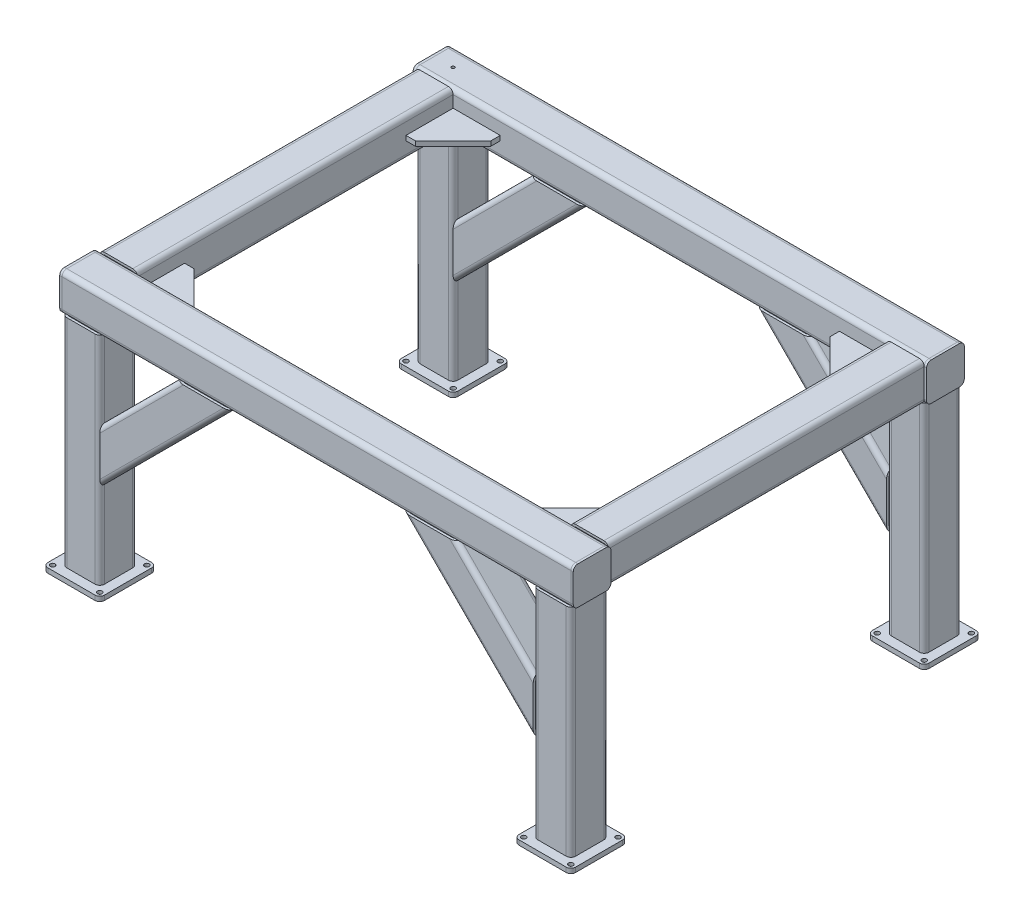
SolidWorks part; units mm, degrees
material "AISI 304"
ref_plane "Front Plane" through (0, 0, 0) normal (0, 0, 1) x (1, 0, 0)
ref_plane "Top Plane" through (0, 0, 0) normal (0, 1, 0) x (1, 0, 0)
ref_plane "Right Plane" through (0, 0, 0) normal (1, 0, 0) x (0, 0, -1)
sketch "Sketch1" plane through (0, 0, 0) normal (0, 1, 0) x (1, 0, 0)
  line L1 (-500, 375) -> (500, 375)
  line L2 (-500, 375) -> (-500, -375)
  line L3 (-500, -375) -> (500, -375)
  line L4 (500, 375) -> (500, -375)
  line L5 (-500, 375) -> (500, -375) construction
  line L6 (-500, -375) -> (500, 375) construction
  point P0 (0, 0)
  dimension "D1" = 750
  dimension "D2" = 1000
sketch3d "3DSketch1"
  line L0 (-500, 0, 375) -> (-500, -500, 375)
  line L1 (500, 0, 375) -> (500, -500, 375)
  line L2 (500, 0, -375) -> (500, -500, -375)
  line L3 (-500, 0, -375) -> (-500, -500, -375)
  line L4 (-500, -300, 375) -> (-200, 0, 375)
  line L5 (-500, 0, 375) -> (500, 0, 375) construction
  line L6 (500, -300, 375) -> (200, 0, 375)
  line L7 (-200, 0, -375) -> (-500, -300, -375)
  line L8 (-500, 0, -375) -> (500, 0, -375) construction
  line L9 (500, -300, -375) -> (200, 0, -375)
  dimension "D1" = 500
  dimension "D2" = 45
  dimension "D3" = 45
  dimension "D4" = 45
  dimension "D5" = 45
  dimension "D6" = 200
  dimension "D7" = 200
  dimension "D8" = 200
  dimension "D9" = 200
other "Square tube 80 X 80 X 5(1)"
ref_plane "Plane1" through (-500, 0, 375) normal (1, 0, 0) x (0, 0, -1)
sketch "Sketch11" plane through (-500, 0, 375) normal (1, 0, 0) x (0, 0, -1)
  line L0 (-30, -35) -> (30, -35)
  line L1 (-35, -30) -> (-35, 30)
  line L2 (30, 35) -> (-30, 35)
  line L3 (35, 30) -> (35, -30)
  line L4 (-30, -40) -> (30, -40)
  line L5 (-40, -30) -> (-40, 30)
  line L6 (30, 40) -> (-30, 40)
  line L7 (40, 30) -> (40, -30)
  arc A0 (40, 30) -> (30, 40) centre (30, 30) ccw
  arc A1 (30, -40) -> (40, -30) centre (30, -30) ccw
  arc A2 (-40, -30) -> (-30, -40) centre (-30, -30) ccw
  arc A3 (-30, 40) -> (-40, 30) centre (-30, 30) ccw
  arc A4 (-30, 35) -> (-35, 30) centre (-30, 30) ccw
  arc A5 (35, 30) -> (30, 35) centre (30, 30) ccw
  arc A6 (30, -35) -> (35, -30) centre (30, -30) ccw
  arc A7 (-35, -30) -> (-30, -35) centre (-30, -30) ccw
  point P0 (-40, 0)
  point P1 (40, 0)
  point P2 (0, 40)
  point P3 (0, -40)
  point P4 (0, 0)
  point P5 (-40, -40)
  point P6 (40, -40)
  point P7 (40, 40)
  point P8 (-40, 40)
  point P33 (0, 0)
  dimension "D1" = 10
  dimension "Thickness" = 5
  dimension "V_leg" = 80
other "Square tube 80 X 80 X 5(2)"
ref_plane "Plane2" through (500, 0, 375) normal (0, -1, 0) x (1, 0, 0)
sketch "Sketch12" plane through (500, 0, 375) normal (0, -1, 0) x (1, 0, 0)
  line L0 (-30, -35) -> (30, -35)
  line L1 (-35, -30) -> (-35, 30)
  line L2 (30, 35) -> (-30, 35)
  line L3 (35, 30) -> (35, -30)
  line L4 (-30, -40) -> (30, -40)
  line L5 (-40, -30) -> (-40, 30)
  line L6 (30, 40) -> (-30, 40)
  line L7 (40, 30) -> (40, -30)
  arc A0 (40, 30) -> (30, 40) centre (30, 30) ccw
  arc A1 (30, -40) -> (40, -30) centre (30, -30) ccw
  arc A2 (-40, -30) -> (-30, -40) centre (-30, -30) ccw
  arc A3 (-30, 40) -> (-40, 30) centre (-30, 30) ccw
  arc A4 (-30, 35) -> (-35, 30) centre (-30, 30) ccw
  arc A5 (35, 30) -> (30, 35) centre (30, 30) ccw
  arc A6 (30, -35) -> (35, -30) centre (30, -30) ccw
  arc A7 (-35, -30) -> (-30, -35) centre (-30, -30) ccw
  point P0 (-40, 0)
  point P1 (40, 0)
  point P2 (0, 40)
  point P3 (0, -40)
  point P4 (0, 0)
  point P5 (-40, -40)
  point P6 (40, -40)
  point P7 (40, 40)
  point P8 (-40, 40)
  point P33 (0, 0)
  dimension "D1" = 10
  dimension "Thickness" = 5
  dimension "V_leg" = 80
other "Square tube 80 X 80 X 5(3)"
ref_plane "Plane3" through (500, -300, 375) normal (-0.7071, 0.7071, 0) x (0.7071, 0.7071, 0)
sketch "Sketch13" plane through (500, -300, 375) normal (-0.7071, 0.7071, 0) x (0.7071, 0.7071, 0)
  line L0 (-30, -35) -> (30, -35)
  line L1 (-35, -30) -> (-35, 30)
  line L2 (30, 35) -> (-30, 35)
  line L3 (35, 30) -> (35, -30)
  line L4 (-30, -40) -> (30, -40)
  line L5 (-40, -30) -> (-40, 30)
  line L6 (30, 40) -> (-30, 40)
  line L7 (40, 30) -> (40, -30)
  arc A0 (40, 30) -> (30, 40) centre (30, 30) ccw
  arc A1 (30, -40) -> (40, -30) centre (30, -30) ccw
  arc A2 (-40, -30) -> (-30, -40) centre (-30, -30) ccw
  arc A3 (-30, 40) -> (-40, 30) centre (-30, 30) ccw
  arc A4 (-30, 35) -> (-35, 30) centre (-30, 30) ccw
  arc A5 (35, 30) -> (30, 35) centre (30, 30) ccw
  arc A6 (30, -35) -> (35, -30) centre (30, -30) ccw
  arc A7 (-35, -30) -> (-30, -35) centre (-30, -30) ccw
  point P0 (-40, 0)
  point P1 (40, 0)
  point P2 (0, 40)
  point P3 (0, -40)
  point P4 (0, 0)
  point P5 (-40, -40)
  point P6 (40, -40)
  point P7 (40, 40)
  point P8 (-40, 40)
  point P33 (0, 0)
  dimension "D1" = 10
  dimension "Thickness" = 5
  dimension "V_leg" = 80
other "Trim/Extend1"
other "Trim/Extend2"
other "Trim/Extend3"
other "Trim/Extend4"
other "Trim/Extend5"
other "Gusset1" parameters "D1"=10, "D2"=10, "D3"=0, "D4"=0, "D10"=5, "D11"=100, "D12"=100, "D13"=20, "D14"=45, "D15"=20
sketch "Sketch14" plane through (-460, 0, -335) normal (0, 1, 0) x (1, 0, 0)
  line L0 (0, 0) -> (0, -100)
  line L1 (0, 0) -> (100, 0)
  line L2 (20, -100) -> (100, -20)
  line L3 (0, -100) -> (20, -100)
  line L4 (100, 0) -> (100, -20)
other "Gusset2" parameters "D1"=10, "D2"=10, "D3"=0, "D4"=0, "D10"=5, "D11"=100, "D12"=100, "D13"=20, "D14"=45, "D15"=20
sketch "Sketch15" plane through (460, 0, -335) normal (0, -1, 0) x (-1, 0, 0)
  line L0 (0, 0) -> (100, 0)
  line L1 (0, 0) -> (0, -100)
  line L2 (100, -20) -> (20, -100)
  line L3 (100, 0) -> (100, -20)
  line L4 (0, -100) -> (20, -100)
other "Gusset3" parameters "D1"=10, "D2"=10, "D3"=0, "D4"=0, "D10"=5, "D11"=100, "D12"=100, "D13"=20, "D14"=45, "D15"=20
sketch "Sketch16" plane through (-460, 0, 335) normal (0, -1, 0) x (-1, 0, 0)
  line L0 (0, 0) -> (0, 100)
  line L1 (0, 0) -> (-100, 0)
  line L2 (-20, 100) -> (-100, 20)
  line L3 (0, 100) -> (-20, 100)
  line L4 (-100, 0) -> (-100, 20)
other "Gusset4" parameters "D1"=10, "D2"=10, "D3"=0, "D4"=0, "D10"=5, "D11"=100, "D12"=100, "D13"=20, "D14"=45, "D15"=20
sketch "Sketch17" plane through (460, 0, 335) normal (0, 1, 0) x (1, 0, 0)
  line L0 (0, 0) -> (-100, 0)
  line L1 (0, 0) -> (0, 100)
  line L2 (-100, 20) -> (-20, 100)
  line L3 (-100, 0) -> (-100, 20)
  line L4 (0, 100) -> (-20, 100)
other "End cap1" parameters "D1"=5, "D2"=3, "D3"=10
sketch "Sketch18" plane through (0, -500, 0) normal (0, -1, 0) x (1, 0, 0)
  line L0 (470, -405) -> (530, -345) construction
  line L1 (550, -315) -> (450, -315)
  line L2 (560, -325) -> (560, -425)
  line L3 (550, -435) -> (450, -435)
  line L4 (440, -325) -> (440, -425)
  line L5 (560, -315) -> (440, -435) construction
  line L6 (560, -435) -> (440, -315) construction
  line L7 (470, -345) -> (530, -405) construction
  arc A0 (450, -435) -> (440, -425) centre (450, -425) cw
  arc A1 (560, -425) -> (550, -435) centre (550, -425) cw
  arc A2 (550, -315) -> (560, -325) centre (550, -325) cw
  arc A3 (450, -315) -> (440, -325) centre (450, -325) ccw
  point P0 (500, -375)
  point P12 (530, -405)
  point P13 (0, 0)
  point P14 (524.5228, -405)
  point P15 (500, -375)
  dimension "D2" = 10
  dimension "D1" = 120
extrude "Boss-Extrude1" add sketch "Sketch18" along normal blind 10 separate body
hole_wizard "Ø10.0mm Dowel Hole1" positions "Sketch19" profile "Sketch21" hole size "Ø10.0" standard "ANSI Metric"
sketch "Sketch19" plane through (0, -510, 0) normal (0, -1, 0) x (-1, 0, 0)
  point P0 (-450, 425)
  point P3 (-450, 325)
  point P6 (-550, 325)
  point P9 (-550, 425)
sketch "Sketch21" plane through (450, -510, -425) normal (1, 0, 0) x (0, 0, -1)
  line L0 (0, 0) -> (0, 13.0043)
  line L1 (0, 13.0043) -> (5, 10)
  line L2 (5, 10) -> (5, 0)
  line L5 (5, 0) -> (0, 0)
  line L10 (0, 13.0043) -> (-5, 10) construction
  line L11 (0, -6.35) -> (0, 107.95) construction
  dimension "Hole Dia." = 10
  dimension "Hole Depth" = 10
  dimension "Drill Angle" = 118
mirror "Mirror1" about plane through (0, 0, 0) normal (0, 0, 1)
mirror "Mirror2" about plane through (0, 0, 0) normal (1, 0, 0)
sketch "Sketch22" plane through (0, 40, 0) normal (0, 1, 0) x (1, 0, 0)
  circle A2 centre (-500, 375) radius 3.3095
  dimension "D1" = 6.619
extrude "Cut-Extrude1" cut sketch "Sketch22" against normal blind 50
